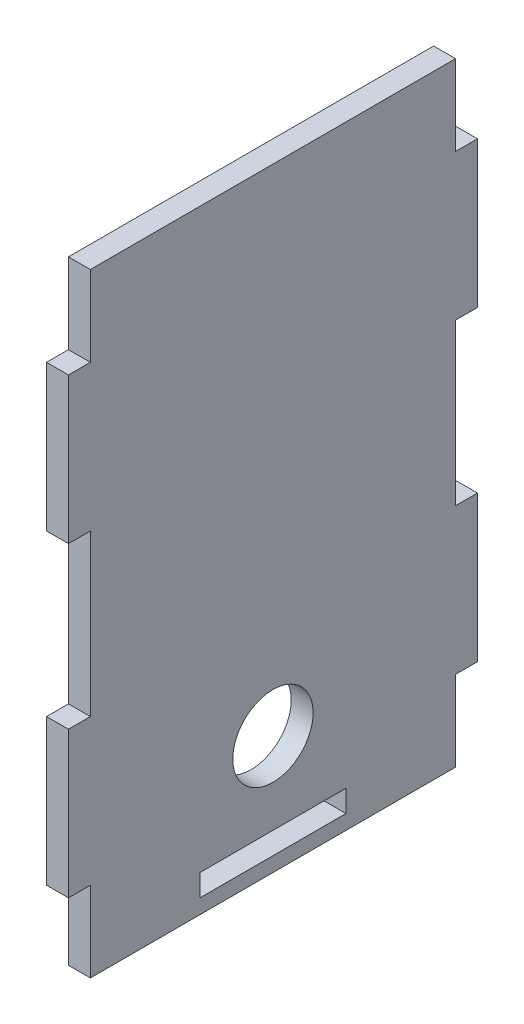
SolidWorks part; units mm, degrees
ref_plane "Front Plane" through (0, 0, 0) normal (0, 0, 1) x (1, 0, 0)
ref_plane "Top Plane" through (0, 0, 0) normal (0, 1, 0) x (1, 0, 0)
ref_plane "Right Plane" through (0, 0, 0) normal (1, 0, 0) x (0, 0, -1)
sketch "Sketch1" plane through (0, 0, 0) normal (1, 0, 0) x (0, 0, -1)
  line L0 (0, 0) -> (0, 3.5) construction
  line L1 (0, 0) -> (50, 0)
  line L2 (0, 0) -> (0, 11)
  line L3 (0, 84) -> (50, 84)
  line L4 (50, 0) -> (50, 11)
  line L5 (0, 3.5) -> (50, 3.5) construction
  line L6 (50, 84) -> (50, 73) construction
  line L7 (15, 2) -> (35, 2)
  line L8 (15, 2) -> (15, 5)
  line L9 (15, 5) -> (35, 5)
  line L10 (35, 2) -> (35, 5)
  line L11 (15, 2) -> (35, 5) construction
  line L12 (15, 5) -> (35, 2) construction
  line L13 (50, 42) -> (50, 53) construction
  line L14 (50, 42) -> (50, 53) construction
  line L15 (50, 42) -> (0, 42) construction
  line L16 (50, 53) -> (53, 53)
  line L18 (50, 73) -> (53, 73)
  line L19 (53, 53) -> (53, 73)
  line L20 (50, 31) -> (50, 53)
  line L21 (50, 11) -> (50, 0) construction
  line L22 (25, 42) -> (25, 84) construction
  line L23 (50, 31) -> (53, 31)
  line L25 (53, 31) -> (53, 11)
  line L26 (50, 11) -> (53, 11)
  line L28 (0, 11) -> (-3, 11)
  line L29 (-3, 31) -> (-3, 11)
  line L30 (0, 31) -> (-3, 31)
  line L31 (0, 73) -> (-3, 73)
  line L32 (-3, 53) -> (-3, 73)
  line L33 (0, 53) -> (-3, 53)
  line L35 (50, 73) -> (50, 84)
  line L36 (50, 53) -> (50, 31) construction
  line L37 (50, 73) -> (50, 84) construction
  line L38 (50, 73) -> (50, 84) construction
  line L39 (0, 31) -> (0, 53)
  line L40 (0, 73) -> (0, 84)
  line L41 (50, 73) -> (53, 53) construction
  line L42 (50, 53) -> (53, 73) construction
  line L43 (39.224, 84) -> (39.224, 0) construction
  line L44 (39.224, 42) -> (39.224, 84) construction
  line L45 (51.5, 63) -> (39.224, 63) construction
  line L46 (25, 5) -> (25, 16.2) construction
  circle A0 centre (25, 16.2) radius 5.5
  point P5 (25, 3.5)
  dimension "D1" = 84
  dimension "D2" = 50
  dimension "D3" = 20
  dimension "D4" = 3
  dimension "D5" = 2
  dimension "D6" = 20
extrude "Boss-Extrude2" add sketch "Sketch1" along normal blind 3
